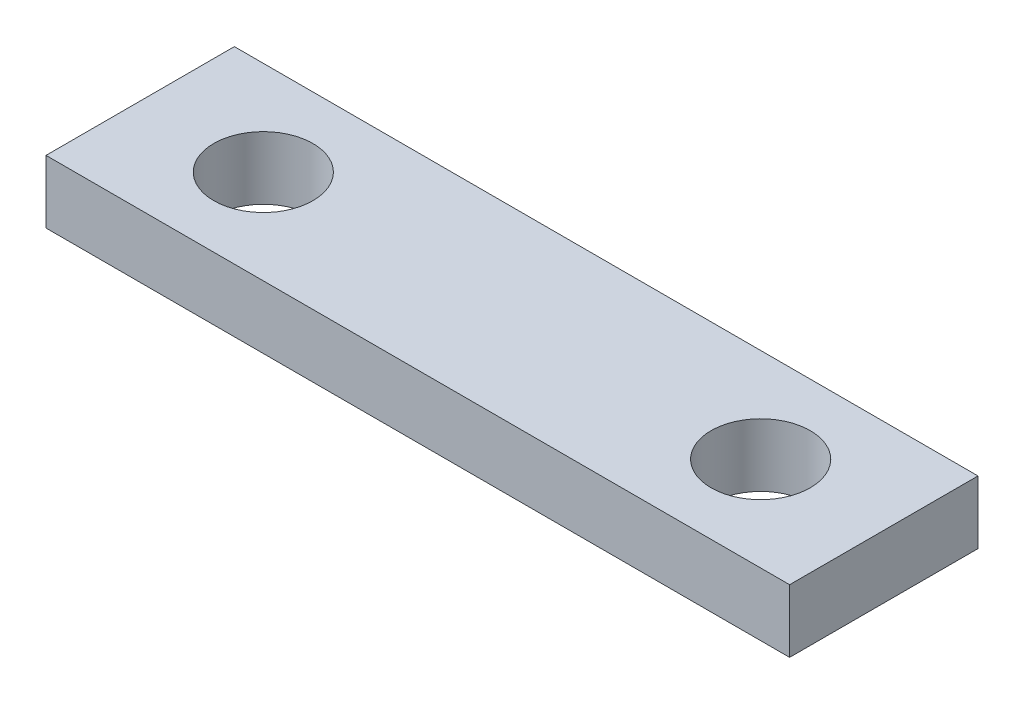
SolidWorks part; units mm, degrees
ref_plane "Front Plane" through (0, 0, 0) normal (0, 0, 1) x (1, 0, 0)
ref_plane "Top Plane" through (0, 0, 0) normal (0, 1, 0) x (1, 0, 0)
ref_plane "Right Plane" through (0, 0, 0) normal (1, 0, 0) x (0, 0, -1)
sketch "Sketch1" plane through (0, 0, 0) normal (0, 1, 0) x (1, 0, 0)
  line L1 (0, 0) -> (-75, 0)
  line L2 (0, 0) -> (0, -19)
  line L3 (0, -19) -> (-75, -19)
  line L4 (-75, 0) -> (-75, -19)
  circle A0 centre (-62.58, -9.5) radius 5
  circle A1 centre (-12.42, -9.5) radius 5
  point P9 (0, 0)
  dimension "D6" = 10
  dimension "D1" = 75
  dimension "D2" = 19
  dimension "D3" = 50.16
  dimension "D4" = 9.5
  dimension "D5" = 12.42
extrude "Boss-Extrude1" add sketch "Sketch1" along normal blind 6.35
